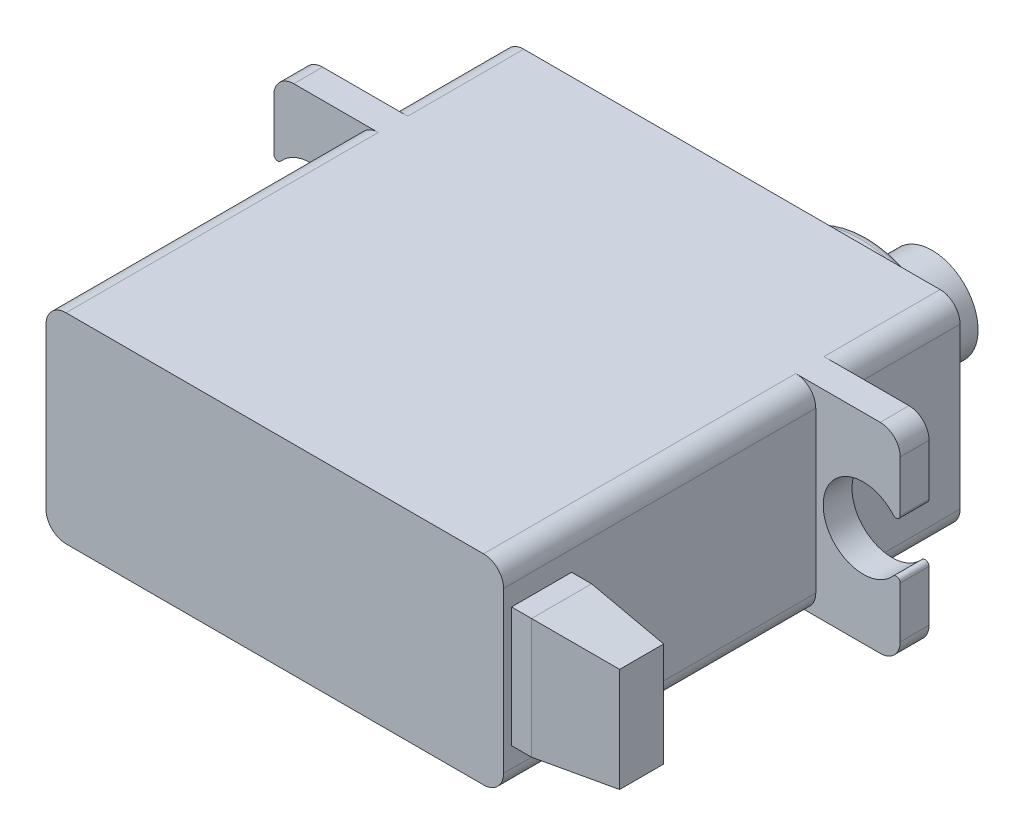
SolidWorks part; units mm, degrees
ref_plane "Front Plane" through (0, 0, 0) normal (0, 0, 1) x (1, 0, 0)
ref_plane "Top Plane" through (0, 0, 0) normal (0, 1, 0) x (1, 0, 0)
ref_plane "Right Plane" through (0, 0, 0) normal (1, 0, 0) x (0, 0, -1)
sketch "Sketch1" plane through (0, 0, 0) normal (0, 0, 1) x (1, 0, 0)
  line L1 (0, 0) -> (39.751, 0)
  line L2 (0, 0) -> (0, 12.7)
  line L3 (0, 12.7) -> (39.751, 12.7)
  line L4 (39.751, 0) -> (39.751, 12.7)
  dimension "D1" = 12.7
  dimension "D2" = 39.751
extrude "Boss-Extrude1" add sketch "Sketch1" along normal blind 1.8288 contours L3 L4 L1 L2
sketch "Sketch2" plane through (0, 0, 1.8288) normal (0, 0, 1) x (1, 0, 0)
  line L0 (0, 0) -> (39.751, 0) construction
  line L1 (5.3594, 0) -> (34.3916, 0)
  line L2 (5.3594, 0) -> (5.3594, 12.7)
  line L3 (5.3594, 12.7) -> (34.3916, 12.7)
  line L4 (34.3916, 0) -> (34.3916, 12.7)
  line L5 (0, 12.7) -> (39.751, 12.7) construction
  point P8 (19.8755, 12.7)
  point P9 (19.8755, 12.7)
  dimension "D1" = 29.0322
extrude "Boss-Extrude2" add sketch "Sketch2" along normal blind 19.812
sketch "Sketch3" plane through (0, 0, 0) normal (0, 0, -1) x (-1, 0, 0)
  line L0 (0, 0) -> (-39.751, 0) construction
  line L1 (-34.3535, 0) -> (-5.3975, 0)
  line L2 (-34.3535, 0) -> (-34.3535, 12.7)
  line L3 (-34.3535, 12.7) -> (-5.3975, 12.7)
  line L4 (-5.3975, 0) -> (-5.3975, 12.7)
  line L5 (0, 12.7) -> (-39.751, 12.7) construction
  point P8 (-19.8755, 12.7)
  point P9 (-19.8755, 12.7)
  dimension "D1" = 28.956
extrude "Boss-Extrude3" add sketch "Sketch3" along normal blind 7.366
sketch "Sketch4" plane through (0, 0, -7.366) normal (0, 0, -1) x (-1, 0, 0)
  line L0 (-34.3535, 12.7) -> (-34.3535, 0) construction
  line L1 (-34.3535, 12.7) -> (-34.3535, 0) construction
  circle A0 centre (-27.2415, 6.35) radius 5.842
  point P2 (0, 0)
  point P5 (-34.3535, 6.35)
  dimension "D2" = 11.684
  dimension "D1" = 7.112
extrude "Boss-Extrude4" add sketch "Sketch4" along normal blind 1.27
sketch "Sketch5" plane through (0, 0, -8.636) normal (0, 0, -1) x (-1, 0, 0)
  circle A0 centre (-27.2415, 6.35) radius 2.921
  dimension "D1" = 5.842
extrude "Boss-Extrude5" add sketch "Sketch5" along normal blind 4.064
sketch "Sketch6" plane through (34.3916, 0, 0) normal (1, 0, 0) x (0, 0, -1)
  line L0 (-21.6408, 0) -> (-21.6408, 12.7) construction
  line L1 (-21.1328, 2.54) -> (-17.3228, 2.54)
  line L2 (-21.1328, 2.54) -> (-21.1328, 10.16)
  line L3 (-21.1328, 10.16) -> (-17.3228, 10.16)
  line L4 (-17.3228, 2.54) -> (-17.3228, 10.16)
  point P4 (-21.1328, 6.35)
  point P7 (-21.6408, 6.35)
  dimension "D1" = 0.508
  dimension "D2" = 3.81
  dimension "D3" = 7.62
extrude "Boss-Extrude6" add sketch "Sketch6" along normal blind 6.35
chamfer "Chamfer1" distance 5.08 distance2 0.508 4 edges at (40.7416, 10.16, 19.2278) (40.7416, 6.35, 17.3228) (40.7416, 2.54, 19.2278) (40.7416, 6.35, 21.1328)
fillet "Fillet1" radius 1.27 12 edges at (39.751, 0, 0.9144) (39.751, 12.7, 0.9144) (0, 12.7, 0.9144) (0, 0, 0.9144) (5.3975, 12.7, -3.683) (5.3594, 12.7, 11.7348) (5.3975, 0, -3.683) (5.3594, 0, 11.7348) (34.3916, 0, 11.7348) (34.3535, 0, -3.683) (34.3535, 12.7, -3.683) (34.3916, 12.7, 11.7348)
sketch "Sketch7" plane through (0, 0, 0) normal (0, 0, -1) x (-1, 0, 0)
  line L0 (-5.3975, 1.27) -> (-5.3975, 11.43) construction
  line L1 (-34.3535, 11.43) -> (-34.3535, 1.27) construction
  circle A0 centre (-37.4015, 6.35) radius 2.54
  circle A1 centre (-2.3495, 6.35) radius 2.54
  point P7 (-5.3975, 6.35)
  dimension "D2" = 5.08
  dimension "D1" = 3.048
  dimension "D3" = 3.048
extrude "Cut-Extrude1" cut sketch "Sketch7" against normal up to next
fillet "Fillet2" radius 0.254 4 edges at (0, 5.3849, 0.9144) (0, 7.3151, 0.9144) (39.751, 7.3151, 0.9144) (39.751, 5.3849, 0.9144)
fillet "Fillet3" radius 0.508 1 edges at (21.3995, 6.35, -8.636)
